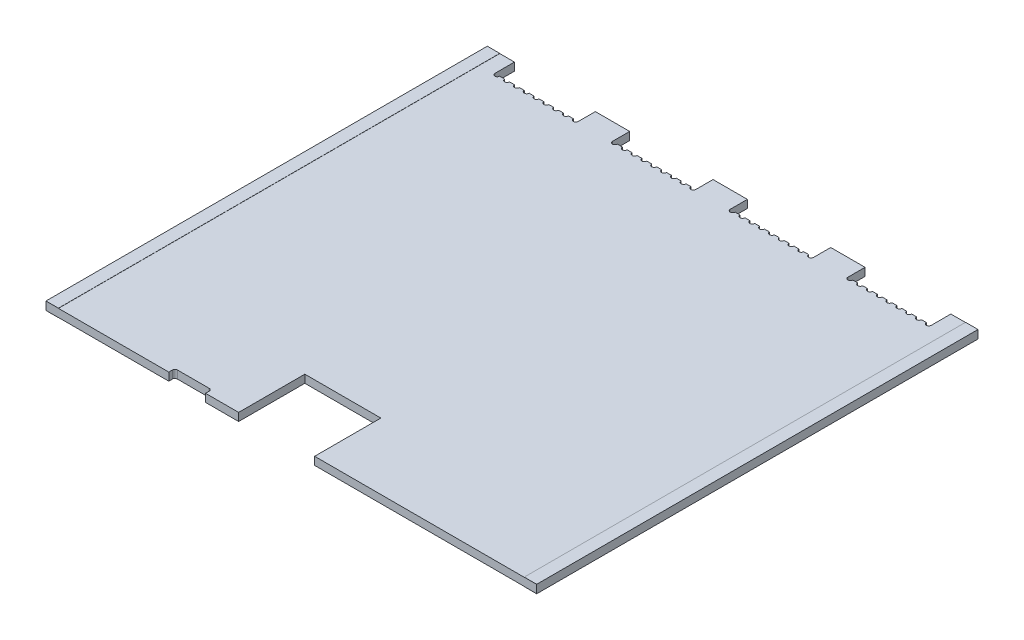
SolidWorks part; units mm, degrees
ref_plane "Front Plane" through (0, 0, 0) normal (0, 0, 1) x (1, 0, 0)
ref_plane "Top Plane" through (0, 0, 0) normal (0, 1, 0) x (1, 0, 0)
ref_plane "Right Plane" through (0, 0, 0) normal (1, 0, 0) x (0, 0, -1)
sketch "Sketch1" plane through (0, 0, 0) normal (0, 1, 0) x (1, 0, 0)
  line L0 (39.25, 0) -> (39.25, 13.5)
  line L1 (0, 90) -> (5.5, 90)
  line L2 (5.5, 90) -> (5.5, 86)
  line L3 (6.5, 86) -> (7.5, 86)
  line L4 (8.5, 86) -> (9.5, 86)
  line L5 (10.5, 86) -> (11.5, 86)
  line L6 (12.5, 86) -> (13.5, 86)
  line L7 (14.5, 86) -> (15.5, 86)
  line L8 (16.5, 86) -> (17.5, 86)
  line L9 (18.5, 86) -> (19.5, 86)
  line L10 (20.5, 86) -> (21.5, 86)
  line L11 (22.5, 86) -> (22.5, 89.5)
  line L12 (22.5, 89.5) -> (29.5, 89.5)
  line L13 (29.5, 89.5) -> (29.5, 86)
  line L14 (30.5, 86) -> (31.5, 86)
  line L15 (32.5, 86) -> (33.5, 86)
  line L16 (34.5, 86) -> (35.5, 86)
  line L17 (36.5, 86) -> (37.5, 86)
  line L18 (38.5, 86) -> (39.5, 86)
  line L19 (40.5, 86) -> (41.5, 86)
  line L20 (42.5, 86) -> (43.5, 86)
  line L21 (44.5, 86) -> (45.5, 86)
  line L22 (46.5, 86) -> (46.5, 89.5)
  line L23 (46.5, 89.5) -> (53.5, 89.5)
  line L24 (53.5, 89.5) -> (53.5, 86)
  line L25 (54.5, 86) -> (55.5, 86)
  line L26 (56.5, 86) -> (57.5, 86)
  line L27 (58.5, 86) -> (59.5, 86)
  line L28 (60.5, 86) -> (61.5, 86)
  line L29 (62.5, 86) -> (63.5, 86)
  line L30 (64.5, 86) -> (65.5, 86)
  line L31 (66.5, 86) -> (67.5, 86)
  line L32 (68.5, 86) -> (69.5, 86)
  line L33 (70.5, 86) -> (70.5, 89.5)
  line L34 (70.5, 89.5) -> (77.5, 89.5)
  line L35 (77.5, 89.5) -> (77.5, 86)
  line L36 (78.5, 86) -> (79.5, 86)
  line L37 (80.5, 86) -> (81.5, 86)
  line L38 (82.5, 86) -> (83.5, 86)
  line L39 (84.5, 86) -> (85.5, 86)
  line L40 (86.5, 86) -> (87.5, 86)
  line L41 (88.5, 86) -> (89.5, 86)
  line L42 (90.5, 86) -> (91.5, 86)
  line L43 (92.5, 86) -> (93.5, 86)
  line L44 (94.5, 86) -> (94.5, 90)
  line L45 (94.5, 90) -> (100, 90)
  line L46 (100, 90) -> (100, 0)
  line L47 (100, 0) -> (54.75, 0)
  line L48 (32.5, 0) -> (32.5, 0.75)
  line L49 (32, 1.25) -> (25.5, 1.25)
  line L50 (25, 0.75) -> (25, 0)
  line L51 (25, 0) -> (13.5, 0)
  line L52 (39.25, 13.5) -> (54.75, 13.5)
  line L53 (54.75, 13.5) -> (54.75, 0)
  line L54 (32.5, 0) -> (39.25, 0)
  line L55 (13.5, 0) -> (0, 0)
  line L56 (0, 0) -> (0, 90)
  arc A0 (5.5, 86) -> (6.5, 86) centre (6, 86) ccw
  arc A1 (7.5, 86) -> (8.5, 86) centre (8, 86) ccw
  arc A2 (9.5, 86) -> (10.5, 86) centre (10, 86) ccw
  arc A3 (11.5, 86) -> (12.5, 86) centre (12, 86) ccw
  arc A4 (13.5, 86) -> (14.5, 86) centre (14, 86) ccw
  arc A5 (15.5, 86) -> (16.5, 86) centre (16, 86) ccw
  arc A6 (17.5, 86) -> (18.5, 86) centre (18, 86) ccw
  arc A7 (19.5, 86) -> (20.5, 86) centre (20, 86) ccw
  arc A8 (21.5, 86) -> (22.5, 86) centre (22, 86) ccw
  arc A9 (29.5, 86) -> (30.5, 86) centre (30, 86) ccw
  arc A10 (31.5, 86) -> (32.5, 86) centre (32, 86) ccw
  arc A11 (33.5, 86) -> (34.5, 86) centre (34, 86) ccw
  arc A12 (35.5, 86) -> (36.5, 86) centre (36, 86) ccw
  arc A13 (37.5, 86) -> (38.5, 86) centre (38, 86) ccw
  arc A14 (39.5, 86) -> (40.5, 86) centre (40, 86) ccw
  arc A15 (41.5, 86) -> (42.5, 86) centre (42, 86) ccw
  arc A16 (43.5, 86) -> (44.5, 86) centre (44, 86) ccw
  arc A17 (45.5, 86) -> (46.5, 86) centre (46, 86) ccw
  arc A18 (53.5, 86) -> (54.5, 86) centre (54, 86) ccw
  arc A19 (55.5, 86) -> (56.5, 86) centre (56, 86) ccw
  arc A20 (57.5, 86) -> (58.5, 86) centre (58, 86) ccw
  arc A21 (59.5, 86) -> (60.5, 86) centre (60, 86) ccw
  arc A22 (61.5, 86) -> (62.5, 86) centre (62, 86) ccw
  arc A23 (63.5, 86) -> (64.5, 86) centre (64, 86) ccw
  arc A24 (65.5, 86) -> (66.5, 86) centre (66, 86) ccw
  arc A25 (67.5, 86) -> (68.5, 86) centre (68, 86) ccw
  arc A26 (69.5, 86) -> (70.5, 86) centre (70, 86) ccw
  arc A27 (77.5, 86) -> (78.5, 86) centre (78, 86) ccw
  arc A28 (79.5, 86) -> (80.5, 86) centre (80, 86) ccw
  arc A29 (81.5, 86) -> (82.5, 86) centre (82, 86) ccw
  arc A30 (83.5, 86) -> (84.5, 86) centre (84, 86) ccw
  arc A31 (85.5, 86) -> (86.5, 86) centre (86, 86) ccw
  arc A32 (87.5, 86) -> (88.5, 86) centre (88, 86) ccw
  arc A33 (89.5, 86) -> (90.5, 86) centre (90, 86) ccw
  arc A34 (91.5, 86) -> (92.5, 86) centre (92, 86) ccw
  arc A35 (93.5, 86) -> (94.5, 86) centre (94, 86) ccw
  arc A36 (32.5, 0.75) -> (32, 1.25) centre (32, 0.75) ccw
  arc A37 (25.5, 1.25) -> (25, 0.75) centre (25.5, 0.75) ccw
extrude "FR4" add sketch "Sketch1" along normal blind 1.6154
sketch "Sketch2" plane through (0, 0, 0) normal (0, 0, 1) x (1, 0, 0)
  line L0 (0, 1.6154) -> (25, 1.6154) construction
  line L1 (2.5, 1.6154) -> (2.5, 1.651)
  line L2 (2.5, 1.651) -> (-0.0356, 1.651)
  line L3 (-0.0356, 1.651) -> (-0.0356, -0.0356)
  line L4 (-0.0356, -0.0356) -> (2.5, -0.0356)
  line L5 (2.5, -0.0356) -> (2.5, 0)
  line L6 (0, 0) -> (25, 0) construction
  line L7 (2.5, 0) -> (0, 0)
  line L8 (0, 0) -> (0, 1.6154)
  line L9 (0, 1.6154) -> (2.5, 1.6154)
  line L10 (-0.0356, 0.9975) -> (0, 0.9975) construction
  line L11 (100, 1.6154) -> (100, 0)
  line L12 (100.0356, -0.0356) -> (100.0356, 1.651)
  line L13 (100.0356, 0.6179) -> (100, 0.6179) construction
  line L14 (97.5, -0.0356) -> (100.0356, -0.0356)
  line L15 (100, 0) -> (97.5, 0)
  line L16 (100.0356, 1.651) -> (97.5, 1.651)
  line L17 (97.5, 1.6154) -> (100, 1.6154)
  line L18 (97.5, 0) -> (97.5, -0.0356)
  line L19 (97.5, 1.651) -> (97.5, 1.6154)
extrude "gold-plating" add sketch "Sketch2" against normal through all separate body
ref_plane "center-of-slot" through (0, 0.8077, 0) normal (0, 1, 0) x (1, 0, 0)
